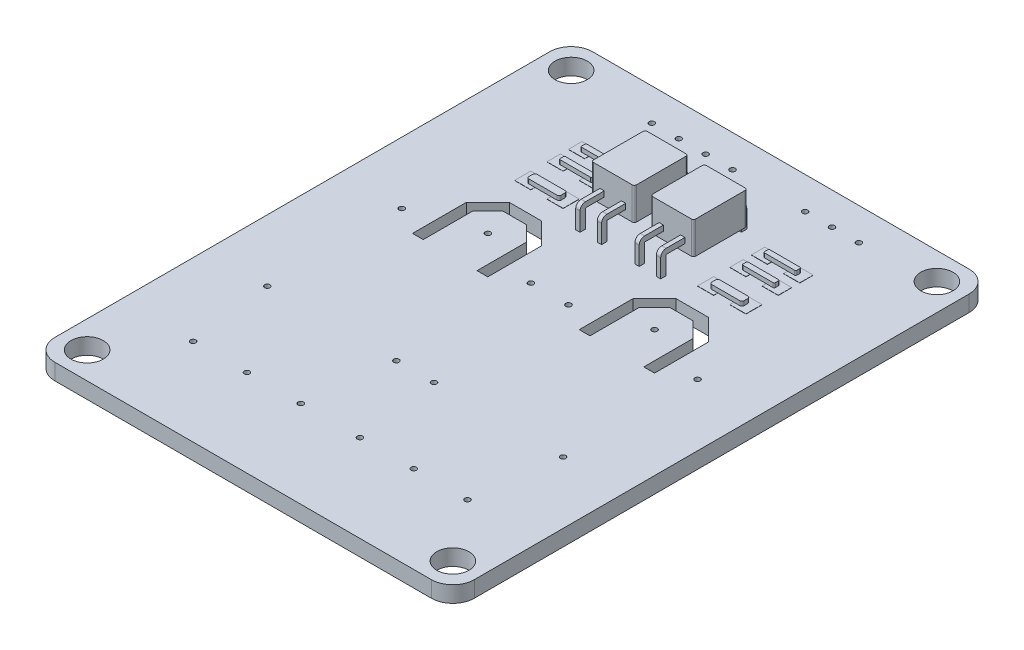
SolidWorks part; units mm, degrees
ref_plane "Ön Düzlem" through (0, 0, 0) normal (0, 0, 1) x (1, 0, 0)
ref_plane "Üst Düzlem" through (0, 0, 0) normal (0, 1, 0) x (1, 0, 0)
ref_plane "Sağ Düzlem" through (0, 0, 0) normal (1, 0, 0) x (0, 0, -1)
sketch "Çizim1" plane through (0, 0, 0) normal (0, 1, 0) x (1, 0, 0)
  line L0 (0, 0) -> (0, 25) construction
  line L1 (-17.5, 25) -> (17.5, 25)
  line L2 (-19.5, 23) -> (-19.5, -23)
  line L3 (-17.5, -25) -> (17.5, -25)
  line L4 (19.5, 23) -> (19.5, -23)
  line L5 (-19.5, 25) -> (19.5, -25) construction
  line L6 (-19.5, -25) -> (19.5, 25) construction
  line L7 (0, 25) -> (0, 0) construction
  line L8 (0, 0) -> (19.5, 0) construction
  line L9 (-13.75, 25) -> (-13.75, -25) construction
  line L10 (-19.5, -9) -> (19.5, -9) construction
  line L11 (-19.5, 3.5) -> (19.5, 3.5) construction
  line L12 (-1.75, 25) -> (-1.75, -25) construction
  line L13 (-19.5, 5.5) -> (19.5, 5.5) construction
  line L14 (-7.75, 5.5) -> (-7.75, -25) construction
  line L15 (-19.5, -16.89) -> (19.5, -16.89) construction
  line L16 (-11.25, 7) -> (-9.25, 9)
  line L17 (-9.25, 9) -> (-6.25, 9)
  line L18 (-11.25, 7) -> (-11.25, 2)
  line L20 (-4.25, 7) -> (-4.25, 2)
  line L21 (-11.25, 9) -> (-4.25, 2) construction
  line L22 (-11.25, 2) -> (-4.25, 9) construction
  line L24 (-5.25, 6.5858) -> (-5.25, 2)
  line L26 (-8.8358, 8) -> (-6.6642, 8)
  line L27 (-10.25, 6.5858) -> (-8.8358, 8)
  line L28 (-10.25, 6.5858) -> (-10.25, 2)
  line L30 (-11.25, 2) -> (-10.25, 2)
  line L31 (-5.25, 2) -> (-4.25, 2)
  line L32 (-6.25, 9) -> (-4.25, 7)
  line L33 (-6.6642, 8) -> (-5.25, 6.5858) construction
  line L34 (-6.25, 9) -> (-4.25, 7) construction
  line L35 (-6.6642, 8) -> (-5.25, 6.5858)
  line L36 (5.25, 2) -> (4.25, 2)
  line L37 (4.25, 7) -> (4.25, 2)
  line L38 (5.25, 6.5858) -> (5.25, 2)
  line L39 (6.6642, 8) -> (5.25, 6.5858)
  line L40 (6.25, 9) -> (4.25, 7)
  line L41 (8.8358, 8) -> (6.6642, 8)
  line L42 (9.25, 9) -> (6.25, 9)
  line L43 (10.25, 6.5858) -> (8.8358, 8)
  line L44 (11.25, 7) -> (9.25, 9)
  line L45 (10.25, 6.5858) -> (10.25, 2)
  line L46 (11.25, 7) -> (11.25, 2)
  line L47 (11.25, 2) -> (10.25, 2)
  line L48 (-19.5, 22) -> (19.5, 22) construction
  line L49 (7.75, 5.5) -> (7.75, 25) construction
  arc A0 (17.5, -25) -> (19.5, -23) centre (17.5, -23) ccw
  arc A1 (-19.5, -23) -> (-17.5, -25) centre (-17.5, -23) ccw
  arc A2 (17.5, 25) -> (19.5, 23) centre (17.5, 23) cw
  arc A3 (-17.5, 25) -> (-19.5, 23) centre (-17.5, 23) ccw
  circle A4 centre (-17, 22.5) radius 1.5
  circle A5 centre (17, 22.5) radius 1.5
  circle A6 centre (17, -22.5) radius 1.5
  circle A7 centre (-17, -22.5) radius 1.5
  circle A8 centre (-13.75, -9) radius 0.25
  circle A10 centre (-1.75, -9) radius 0.25
  circle A11 centre (-13.75, 3.5) radius 0.25
  circle A12 centre (-7.75, 5.5) radius 0.25
  circle A13 centre (-1.75, 3.5) radius 0.25
  circle A14 centre (13.75, 3.5) radius 0.25
  circle A15 centre (7.75, 5.5) radius 0.25
  circle A16 centre (1.75, 3.5) radius 0.25
  circle A17 centre (1.75, -9) radius 0.25
  circle A18 centre (13.75, -9) radius 0.25
  circle A19 centre (-7.75, -16.89) radius 0.25
  circle A20 centre (-2.75, -16.89) radius 0.25
  circle A21 centre (-12.75, -16.89) radius 0.25
  circle A22 centre (2.75, -16.89) radius 0.25
  circle A23 centre (7.75, -16.89) radius 0.25
  circle A24 centre (12.75, -16.89) radius 0.25
  circle A25 centre (-1.5, 22) radius 0.25
  circle A26 centre (-4, 22) radius 0.25
  circle A27 centre (-6.5, 22) radius 0.25
  circle A28 centre (-9, 22) radius 0.25
  circle A29 centre (7.75, 22) radius 0.25
  circle A30 centre (10.25, 22) radius 0.25
  circle A31 centre (5.25, 22) radius 0.25
  point P0 (0, 0)
  dimension "D3" = 2
  dimension "D4" = 3
  dimension "D6" = 2.5
  dimension "D9" = 0.5
  dimension "D15" = 0.5
  dimension "D16" = 5
  dimension "D17" = 5
  dimension "D24" = 0.5
  dimension "D25" = 1.5
  dimension "D26" = 2.5
  dimension "D27" = 2.5
  dimension "D28" = 2.5
  dimension "D29" = 0.5
  dimension "D30" = 2.5
  dimension "D31" = 2.5
  dimension "D1" = 39
  dimension "D2" = 50
  dimension "D5" = 2.5
  dimension "D7" = 5.75
  dimension "D8" = 16
  dimension "D10" = 12.5
  dimension "D11" = 12
  dimension "D12" = 2
  dimension "D13" = 6
  dimension "D14" = 8.11
  dimension "D18" = 7
  dimension "D19" = 7
  dimension "D21" = 3
  dimension "D20" = 1
extrude "Yükseklik-Ekstrüzyon1" add sketch "Çizim1" along normal blind 1.5
sketch "Çizim2" plane through (0, 1.5, 0) normal (0, 1, 0) x (1, 0, 0)
  line L0 (0, 0) -> (0, 25) construction
  line L1 (17.5, 25) -> (-17.5, 25) construction
  line L2 (-7.75, 9) -> (-7.75, 25) construction
  line L3 (-6.25, 9) -> (-9.25, 9) construction
  line L4 (-7.75, 11) -> (-19.5, 11) construction
  line L5 (-19.5, 23) -> (-19.5, -23) construction
  line L6 (-7.75, 14) -> (-19.5, 14) construction
  line L7 (-19.5, 16) -> (-7.75, 16) construction
  line L8 (-9.25, 9) -> (-9.25, 16) construction
  line L9 (7.75, 12.5) -> (6.25, 12.5)
  line L10 (-7.75, 11) -> (-6.25, 11)
  line L11 (-7.75, 11) -> (-7.75, 12.5)
  line L12 (-7.75, 12.5) -> (-6.25, 12.5)
  line L13 (-6.25, 11) -> (-6.25, 12.5)
  line L14 (-9.25, 11) -> (-10.75, 11)
  line L15 (-9.25, 11) -> (-9.25, 12.5)
  line L16 (-9.25, 12.5) -> (-10.75, 12.5)
  line L17 (-10.75, 11) -> (-10.75, 12.5)
  line L18 (-7.75, 14) -> (-6.25, 14)
  line L19 (-7.75, 14) -> (-7.75, 15.25)
  line L20 (-7.75, 15.25) -> (-6.25, 15.25)
  line L21 (-6.25, 14) -> (-6.25, 15.25)
  line L22 (-9.25, 14) -> (-10.75, 14)
  line L23 (-9.25, 14) -> (-9.25, 15.25)
  line L24 (-9.25, 15.25) -> (-10.75, 15.25)
  line L25 (-10.75, 14) -> (-10.75, 15.25)
  line L26 (-7.75, 16) -> (-6.25, 16)
  line L27 (-7.75, 16) -> (-7.75, 17.25)
  line L28 (-7.75, 17.25) -> (-6.25, 17.25)
  line L29 (-6.25, 16) -> (-6.25, 17.25)
  line L30 (-9.25, 16) -> (-10.75, 16)
  line L31 (-9.25, 16) -> (-9.25, 17.25)
  line L32 (-9.25, 17.25) -> (-10.75, 17.25)
  line L33 (-10.75, 16) -> (-10.75, 17.25)
  line L34 (6.25, 11) -> (6.25, 12.5)
  line L35 (7.75, 11) -> (6.25, 11)
  line L36 (7.75, 11) -> (7.75, 12.5)
  line L37 (9.25, 12.5) -> (10.75, 12.5)
  line L38 (10.75, 11) -> (10.75, 12.5)
  line L39 (9.25, 11) -> (10.75, 11)
  line L40 (9.25, 11) -> (9.25, 12.5)
  line L41 (7.75, 15.25) -> (6.25, 15.25)
  line L42 (6.25, 14) -> (6.25, 15.25)
  line L43 (7.75, 14) -> (6.25, 14)
  line L44 (7.75, 14) -> (7.75, 15.25)
  line L45 (9.25, 15.25) -> (10.75, 15.25)
  line L46 (10.75, 14) -> (10.75, 15.25)
  line L47 (9.25, 14) -> (10.75, 14)
  line L48 (9.25, 14) -> (9.25, 15.25)
  line L49 (7.75, 17.25) -> (6.25, 17.25)
  line L50 (6.25, 16) -> (6.25, 17.25)
  line L51 (7.75, 16) -> (6.25, 16)
  line L52 (7.75, 16) -> (7.75, 17.25)
  line L53 (9.25, 17.25) -> (10.75, 17.25)
  line L54 (10.75, 16) -> (10.75, 17.25)
  line L55 (9.25, 16) -> (10.75, 16)
  line L56 (9.25, 16) -> (9.25, 17.25)
  dimension "D1" = 2
  dimension "D2" = 3
  dimension "D3" = 2
  dimension "D4" = 1.5
  dimension "D5" = 1.5
  dimension "D6" = 1.5
  dimension "D7" = 1.5
  dimension "D8" = 1.25
  dimension "D9" = 1.5
  dimension "D10" = 1.25
  dimension "D11" = 1.5
  dimension "D12" = 1.25
  dimension "D13" = 1.25
  dimension "D14" = 1.5
  dimension "D15" = 1.5
extrude "Yükseklik-Ekstrüzyon2" add sketch "Çizim2" along normal blind 0.02
sketch "Çizim3" plane through (0, 1.52, 0) normal (0, 1, 0) x (1, 0, 0)
  line L0 (-10.75, 11.75) -> (-6.25, 11.75) construction
  line L1 (-10.75, 12.5) -> (-10.75, 11) construction
  line L2 (-6.25, 11) -> (-6.25, 12.5) construction
  line L3 (-6.25, 11.75) -> (-8.5, 11.75) construction
  line L4 (-8.5, 11.75) -> (-8.5, 16.3146) construction
  line L5 (-10.75, 14.625) -> (-6.25, 14.625) construction
  line L6 (-10.75, 15.25) -> (-10.75, 14) construction
  line L7 (-6.25, 14) -> (-6.25, 15.25) construction
  line L8 (-10.75, 16.625) -> (-6.25, 16.625) construction
  line L9 (-10.75, 17.25) -> (-10.75, 16) construction
  line L10 (-6.25, 16) -> (-6.25, 17.25) construction
  line L11 (0, 0) -> (0, 25.4202) construction
  line L12 (-9.9, 16.875) -> (-7.1, 16.875)
  line L13 (-10, 16.775) -> (-10, 16.475)
  line L14 (-9.9, 16.375) -> (-7.1, 16.375)
  line L15 (-7, 16.775) -> (-7, 16.475)
  line L16 (-10, 16.875) -> (-7, 16.375) construction
  line L17 (-10, 16.375) -> (-7, 16.875) construction
  line L18 (-9.9, 14.875) -> (-7.1, 14.875)
  line L19 (-10, 14.775) -> (-10, 14.475)
  line L20 (-9.9, 14.375) -> (-7.1, 14.375)
  line L21 (-7, 14.775) -> (-7, 14.475)
  line L22 (-10, 14.875) -> (-7, 14.375) construction
  line L23 (-10, 14.375) -> (-7, 14.875) construction
  line L24 (-9.8, 12.125) -> (-7.2, 12.125)
  line L25 (-10, 11.925) -> (-10, 11.575)
  line L26 (-9.8, 11.375) -> (-7.2, 11.375)
  line L27 (-7, 11.925) -> (-7, 11.575)
  line L28 (-10, 12.125) -> (-7, 11.375) construction
  line L29 (-10, 11.375) -> (-7, 12.125) construction
  line L30 (9.9, 16.375) -> (7.1, 16.375)
  line L31 (7, 16.775) -> (7, 16.475)
  line L32 (9.9, 16.875) -> (7.1, 16.875)
  line L33 (10, 16.775) -> (10, 16.475)
  line L34 (9.9, 14.375) -> (7.1, 14.375)
  line L35 (7, 14.775) -> (7, 14.475)
  line L36 (9.9, 14.875) -> (7.1, 14.875)
  line L37 (10, 14.775) -> (10, 14.475)
  line L38 (9.8, 11.375) -> (7.2, 11.375)
  line L39 (7, 11.925) -> (7, 11.575)
  line L40 (9.8, 12.125) -> (7.2, 12.125)
  line L41 (10, 11.925) -> (10, 11.575)
  arc A0 (-7.1, 14.375) -> (-7, 14.475) centre (-7.1, 14.475) ccw
  arc A1 (-7.1, 14.875) -> (-7, 14.775) centre (-7.1, 14.775) cw
  arc A2 (-10, 14.475) -> (-9.9, 14.375) centre (-9.9, 14.475) ccw
  arc A3 (-9.9, 14.875) -> (-10, 14.775) centre (-9.9, 14.775) ccw
  arc A4 (-7.1, 16.375) -> (-7, 16.475) centre (-7.1, 16.475) ccw
  arc A5 (-7.1, 16.875) -> (-7, 16.775) centre (-7.1, 16.775) cw
  arc A6 (-10, 16.475) -> (-9.9, 16.375) centre (-9.9, 16.475) ccw
  arc A7 (-9.9, 16.875) -> (-10, 16.775) centre (-9.9, 16.775) ccw
  arc A8 (-7.2, 11.375) -> (-7, 11.575) centre (-7.2, 11.575) ccw
  arc A9 (-7.2, 12.125) -> (-7, 11.925) centre (-7.2, 11.925) cw
  arc A10 (-10, 11.575) -> (-9.8, 11.375) centre (-9.8, 11.575) ccw
  arc A11 (-9.8, 12.125) -> (-10, 11.925) centre (-9.8, 11.925) ccw
  arc A12 (7.1, 16.375) -> (7, 16.475) centre (7.1, 16.475) cw
  arc A13 (7.1, 16.875) -> (7, 16.775) centre (7.1, 16.775) ccw
  arc A14 (10, 16.475) -> (9.9, 16.375) centre (9.9, 16.475) cw
  arc A15 (9.9, 16.875) -> (10, 16.775) centre (9.9, 16.775) cw
  arc A16 (7.1, 14.375) -> (7, 14.475) centre (7.1, 14.475) cw
  arc A17 (7.1, 14.875) -> (7, 14.775) centre (7.1, 14.775) ccw
  arc A18 (10, 14.475) -> (9.9, 14.375) centre (9.9, 14.475) cw
  arc A19 (9.9, 14.875) -> (10, 14.775) centre (9.9, 14.775) cw
  arc A20 (7.2, 11.375) -> (7, 11.575) centre (7.2, 11.575) cw
  arc A21 (7.2, 12.125) -> (7, 11.925) centre (7.2, 11.925) ccw
  arc A22 (10, 11.575) -> (9.8, 11.375) centre (9.8, 11.575) cw
  arc A23 (9.8, 12.125) -> (10, 11.925) centre (9.8, 11.925) cw
  point P20 (-8.5, 16.625)
  point P25 (-8.5, 14.625)
  dimension "D5" = 0.1
  dimension "D6" = 0.2
  dimension "D1" = 0.5
  dimension "D2" = 3
  dimension "D3" = 0.5
  dimension "D4" = 0.75
extrude "Yükseklik-Ekstrüzyon3" add sketch "Çizim3" along normal blind 0.4
ref_plane "Düzlem2" through (0, 2.5, 0) normal (0, 1, 0) x (1, 0, 0)
sketch "Çizim5" plane through (0, 2.5, 0) normal (0, 1, 0) x (1, 0, 0)
  line L0 (0, 0) -> (0, 27.9522) construction
  line L1 (-10, 14.625) -> (0, 14.625) construction
  line L2 (-10, 14.775) -> (-10, 14.475) construction
  line L3 (4.55, 12.125) -> (0.95, 12.125)
  line L4 (-4.55, 17.125) -> (-0.95, 17.125)
  line L5 (-4.75, 16.925) -> (-4.75, 12.325)
  line L6 (-4.55, 12.125) -> (-0.95, 12.125)
  line L7 (-0.75, 16.925) -> (-0.75, 12.325)
  line L8 (-4.75, 17.125) -> (-0.75, 12.125) construction
  line L9 (-4.75, 12.125) -> (-0.75, 17.125) construction
  line L10 (0.75, 16.925) -> (0.75, 12.325)
  line L11 (4.55, 17.125) -> (0.95, 17.125)
  line L12 (4.75, 16.925) -> (4.75, 12.325)
  arc A0 (-0.95, 12.125) -> (-0.75, 12.325) centre (-0.95, 12.325) ccw
  arc A1 (-4.75, 12.325) -> (-4.55, 12.125) centre (-4.55, 12.325) ccw
  arc A2 (-0.95, 17.125) -> (-0.75, 16.925) centre (-0.95, 16.925) cw
  arc A3 (-4.55, 17.125) -> (-4.75, 16.925) centre (-4.55, 16.925) ccw
  arc A4 (0.95, 12.125) -> (0.75, 12.325) centre (0.95, 12.325) cw
  arc A5 (0.95, 17.125) -> (0.75, 16.925) centre (0.95, 16.925) ccw
  arc A6 (4.75, 12.325) -> (4.55, 12.125) centre (4.55, 12.325) cw
  arc A7 (4.55, 17.125) -> (4.75, 16.925) centre (4.55, 16.925) cw
  point P7 (-2.75, 14.625)
  dimension "D4" = 0.2
  dimension "D1" = 5
  dimension "D2" = 4
  dimension "D3" = 0.75
extrude "Yükseklik-Ekstrüzyon4" add sketch "Çizim5" along normal blind 3 separate body
ref_plane "Düzlem3" through (-3.75, 0, 0) normal (-1, 0, 0) x (0, 0, 1)
sketch "Çizim8" plane through (-3.75, 0, 0) normal (-1, 0, 0) x (0, 0, 1)
  line L0 (-14.625, 2.5) -> (-14.625, 0) construction
  line L1 (-16.925, 2.5) -> (-12.325, 2.5) construction
  line L2 (-23, 0) -> (23, 0) construction
  line L3 (-17.375, 3.2109) -> (-10.375, 3.2109)
  line L5 (-17.875, 0.7988) -> (-17.875, 3.2109)
  line L6 (-17.375, 3.7109) -> (-10.375, 3.7109)
  line L7 (-9.875, 0.7988) -> (-9.875, 3.2109)
  line L8 (-10.375, 0.7988) -> (-9.875, 0.7988)
  line L9 (-17.875, 3.7109) -> (-14.625, 0) construction
  line L10 (-10.375, 0.7988) -> (-10.375, 3.2109)
  line L12 (-17.375, 0.7988) -> (-17.375, 3.2109)
  line L13 (-17.875, 0.7988) -> (-17.375, 0.7988)
  line L14 (-17.875, -3.7109) -> (-17.875, 3.7109) construction
  line L15 (-17.375, -3.2109) -> (-17.375, 3.2109) construction
  line L16 (-14.625, 0) -> (-9.875, 3.7109) construction
  line L17 (-17.875, 3.7109) -> (-9.875, 3.7109) construction
  line L18 (-10.375, -3.2109) -> (-10.375, 3.2109) construction
  line L19 (-9.875, -3.7109) -> (-9.875, 3.7109) construction
  line L21 (-17.375, -3.2109) -> (-10.375, -3.2109) construction
  line L22 (-17.875, -3.7109) -> (-9.875, -3.7109) construction
  arc A0 (-10.375, 3.7109) -> (-9.875, 3.2109) centre (-10.375, 3.2109) cw
  arc A1 (-17.875, 3.2109) -> (-17.375, 3.7109) centre (-17.375, 3.2109) cw
  dimension "D3" = 0.5
  dimension "D1" = 8
  dimension "D2" = 0.5
extrude "Yükseklik-Ekstrüzyon5" add sketch "Çizim8" along normal blind 0.2 and the other way blind 0.2
ref_plane "Düzlem4" through (-1.75, 0, 0) normal (1, 0, 0) x (0, 0, -1)
sketch "Çizim9" plane through (-1.75, 0, 0) normal (1, 0, 0) x (0, 0, -1)
  line L0 (14.625, 2.5) -> (14.625, 0) construction
  line L1 (12.325, 2.5) -> (16.925, 2.5) construction
  line L2 (-23, 0) -> (23, 0) construction
  line L3 (10.3784, 0.5594) -> (10.3784, 3.2109)
  line L5 (9.8784, 0.5594) -> (9.8784, 3.2109)
  line L6 (10.3784, 3.7109) -> (17.3716, 3.7109)
  line L7 (17.8716, 0.5594) -> (17.8716, 3.2109)
  line L9 (9.8784, 3.7109) -> (14.625, 0) construction
  line L10 (10.3784, 3.2109) -> (17.3716, 3.2109)
  line L11 (17.3716, 0.5594) -> (17.3716, 3.2109)
  line L13 (9.8784, 3.7109) -> (17.8716, 3.7109) construction
  line L14 (17.8716, -3.7109) -> (17.8716, 3.7109) construction
  line L15 (9.8784, -3.7109) -> (9.8784, 3.7109) construction
  line L16 (9.8784, 0.5594) -> (10.3784, 0.5594)
  line L17 (10.3784, -3.2109) -> (10.3784, 3.2109) construction
  line L18 (17.3716, 0.5594) -> (17.8716, 0.5594)
  line L19 (17.3716, -3.2109) -> (17.3716, 3.2109) construction
  line L20 (14.625, 0) -> (17.8716, 3.7109) construction
  line L22 (10.3784, -3.2109) -> (17.3716, -3.2109) construction
  line L24 (9.8784, -3.7109) -> (17.8716, -3.7109) construction
  arc A0 (17.3716, 3.7109) -> (17.8716, 3.2109) centre (17.3716, 3.2109) cw
  arc A1 (9.8784, 3.2109) -> (10.3784, 3.7109) centre (10.3784, 3.2109) cw
  dimension "D2" = 0.5
  dimension "D1" = 0.5
extrude "Yükseklik-Ekstrüzyon6" add sketch "Çizim9" along normal blind 0.2 and the other way blind 0.2
ref_plane "Düzlem5" through (3.75, 0, 0) normal (1, 0, 0) x (0, 0, -1)
sketch "Çizim10" plane through (3.75, 0, 0) normal (1, 0, 0) x (0, 0, -1)
  line L0 (14.625, 2.5) -> (14.625, 0) construction
  line L1 (12.325, 2.5) -> (16.925, 2.5) construction
  line L2 (-23, 0) -> (23, 0) construction
  line L3 (10.375, 0.6252) -> (10.375, 3.2128)
  line L5 (9.875, 0.6252) -> (9.875, 3.2128)
  line L6 (10.375, 3.7128) -> (17.375, 3.7128)
  line L7 (17.875, 0.6252) -> (17.875, 3.2128)
  line L9 (9.875, 3.7128) -> (14.625, 0) construction
  line L10 (10.375, 3.2128) -> (17.375, 3.2128)
  line L11 (17.375, 0.6252) -> (17.375, 3.2128)
  line L13 (9.875, 3.7128) -> (17.875, 3.7128) construction
  line L14 (17.875, -3.7128) -> (17.875, 3.7128) construction
  line L15 (9.875, -3.7128) -> (9.875, 3.7128) construction
  line L16 (9.875, 0.6252) -> (10.375, 0.6252)
  line L17 (10.375, -3.2128) -> (10.375, 3.2128) construction
  line L18 (14.625, 0) -> (17.875, 3.7128) construction
  line L19 (17.375, 0.6252) -> (17.875, 0.6252)
  line L20 (17.375, -3.2128) -> (17.375, 3.2128) construction
  line L21 (9.875, -3.7128) -> (17.875, -3.7128) construction
  line L22 (10.375, -3.2128) -> (17.375, -3.2128) construction
  arc A0 (17.375, 3.7128) -> (17.875, 3.2128) centre (17.375, 3.2128) cw
  arc A1 (9.875, 3.2128) -> (10.375, 3.7128) centre (10.375, 3.2128) cw
  dimension "D2" = 0.5
  dimension "D1" = 0.5
extrude "Yükseklik-Ekstrüzyon7" add sketch "Çizim10" along normal blind 0.2 and the other way blind 0.2
ref_plane "Düzlem6" through (1.75, 0, 0) normal (-1, 0, 0) x (0, 0, 1)
sketch "Çizim11" plane through (1.75, 0, 0) normal (-1, 0, 0) x (0, 0, 1)
  line L0 (-14.625, 2.5) -> (-14.625, 0) construction
  line L1 (-16.925, 2.5) -> (-12.325, 2.5) construction
  line L2 (-23, 0) -> (23, 0) construction
  line L3 (-17.375, 0.556) -> (-17.375, 3.2109)
  line L5 (-17.875, 0.556) -> (-17.875, 3.2109)
  line L6 (-17.375, 3.7109) -> (-10.375, 3.7109)
  line L7 (-9.875, 0.556) -> (-9.875, 3.2109)
  line L8 (-10.375, 0.556) -> (-9.875, 0.556)
  line L9 (-17.875, 3.7109) -> (-14.625, 0) construction
  line L10 (-17.375, 3.2109) -> (-10.375, 3.2109)
  line L11 (-10.375, 0.556) -> (-10.375, 3.2109)
  line L13 (-17.875, 3.7109) -> (-9.875, 3.7109) construction
  line L14 (-9.875, -3.7109) -> (-9.875, 3.7109) construction
  line L15 (-17.875, -3.7109) -> (-17.875, 3.7109) construction
  line L16 (-17.875, 0.556) -> (-17.375, 0.556)
  line L17 (-17.375, -3.2109) -> (-17.375, 3.2109) construction
  line L18 (-14.625, 0) -> (-9.875, 3.7109) construction
  line L20 (-10.375, -3.2109) -> (-10.375, 3.2109) construction
  line L21 (-17.875, -3.7109) -> (-9.875, -3.7109) construction
  line L22 (-17.375, -3.2109) -> (-10.375, -3.2109) construction
  arc A0 (-10.375, 3.7109) -> (-9.875, 3.2109) centre (-10.375, 3.2109) cw
  arc A1 (-17.875, 3.2109) -> (-17.375, 3.7109) centre (-17.375, 3.2109) cw
  dimension "D2" = 0.5
  dimension "D1" = 0.5
extrude "Yükseklik-Ekstrüzyon8" add sketch "Çizim11" along normal blind 0.2 and the other way blind 0.2
